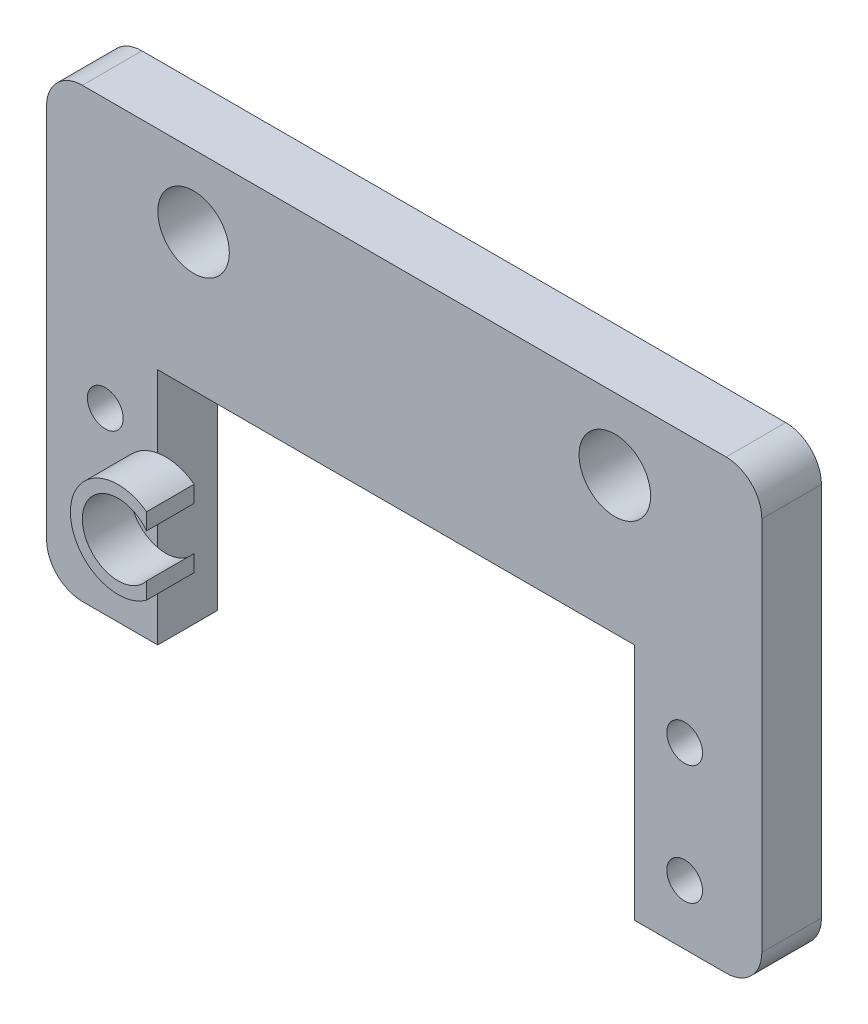
SolidWorks part; units mm, degrees
ref_plane "前视基准面" through (0, 0, 0) normal (0, 0, 1) x (1, 0, 0)
ref_plane "上视基准面" through (0, 0, 0) normal (0, 1, 0) x (1, 0, 0)
ref_plane "右视基准面" through (0, 0, 0) normal (1, 0, 0) x (0, 0, -1)
other "Configuration Table"
sketch "草图1" plane through (0, 0, 0) normal (0, 0, 1) x (1, 0, 0)
  line L0 (0, 0) -> (1.5, 0) construction
  line L2 (-15.5, 27.5) -> (38.5, 27.5)
  line L3 (-18.5, 24.5) -> (-18.5, -7)
  line L4 (-15.5, -10) -> (-9.175, -10)
  line L5 (41.5, 24.5) -> (41.5, -7)
  line L26 (30.825, 10) -> (-9.175, 10)
  line L27 (-9.175, 10) -> (-9.175, -10)
  line L28 (30.825, 10) -> (30.825, -10)
  line L29 (33.3, -10) -> (38.5, -10)
  line L30 (11.5, 18.5) -> (11.5, 10.6886) construction
  line L33 (26.375, 18.5) -> (2.3684, 18.5) construction
  line L34 (33.3, -10) -> (30.825, -10)
  circle A16 centre (-13.575, 5) radius 1.5
  circle A17 centre (-13.575, -5) radius 1.5
  circle A18 centre (35.025, 5) radius 1.5
  circle A19 centre (35.025, -5) radius 1.5
  arc A20 (38.5, 27.5) -> (41.5, 24.5) centre (38.5, 24.5) cw
  arc A21 (38.5, -10) -> (41.5, -7) centre (38.5, -7) ccw
  arc A22 (-18.5, -7) -> (-15.5, -10) centre (-15.5, -7) ccw
  arc A23 (-15.5, 27.5) -> (-18.5, 24.5) centre (-15.5, 24.5) ccw
  circle A32 centre (20.725, 0) radius 5.2518 construction
  dimension "D2" = 3
  dimension "D3" = 3
  dimension "D4" = 60
  dimension "D6" = 3
  dimension "D8" = 14.3
  dimension "D9" = 14.3
  dimension "D10" = 5
  dimension "D11" = 14.875
  dimension "D12" = 10.1
  dimension "D5" = 3
  dimension "D13" = 3
  dimension "D15" = 10
  dimension "D17" = 34.3
  dimension "D18" = 5
  dimension "D7" = 37.5
  dimension "D14" = 10
  dimension "D16" = 34.3
  dimension "D19" = 40
extrude "凸台-拉伸1" add sketch "草图1" along normal blind 5
sketch "草图2" plane through (0, 0, 5) normal (0, 0, 1) x (1, 0, 0)
  line L0 (20.725, 0) -> (20.725, 6.3806) construction
  line L1 (-15.5, 27.5) -> (38.5, 27.5) construction
  line L2 (11.5, 27.5) -> (11.5, 21.5) construction
  line L5 (29.17, 21.5) -> (-6.17, 21.5) construction
  circle A2 centre (-6.17, 21.5) radius 3
  circle A3 centre (29.17, 21.5) radius 3
  dimension "D1" = 6
  dimension "D5" = 6
  dimension "D3" = 35.34
extrude "切除-拉伸1" cut sketch "草图2" against normal blind 10 contours A2 | A3
sketch "草图3" plane through (0, 0, 5) normal (0, 0, 1) x (1, 0, 0)
  circle A1 centre (-8.5, 0) radius 3
extrude "拉伸-薄壁1" add sketch "草图3" along normal blind 4 thin
sketch "草图5" plane through (0, 0, 9) normal (0, 0, 1) x (1, 0, 0)
  line L1 (-6.1151, 3.2113) -> (-6.1151, -3.2113)
  circle A0 centre (-8.5, 0) radius 4 construction
  circle A3 centre (-8.5, 0) radius 4 construction
  arc A4 (-6.1151, -3.2113) -> (-6.1151, 3.2113) centre (-8.5, 0) ccw
  point P3 (-6.1151, 3.2113)
extrude "切除-拉伸2" cut sketch "草图5" against normal blind 4
